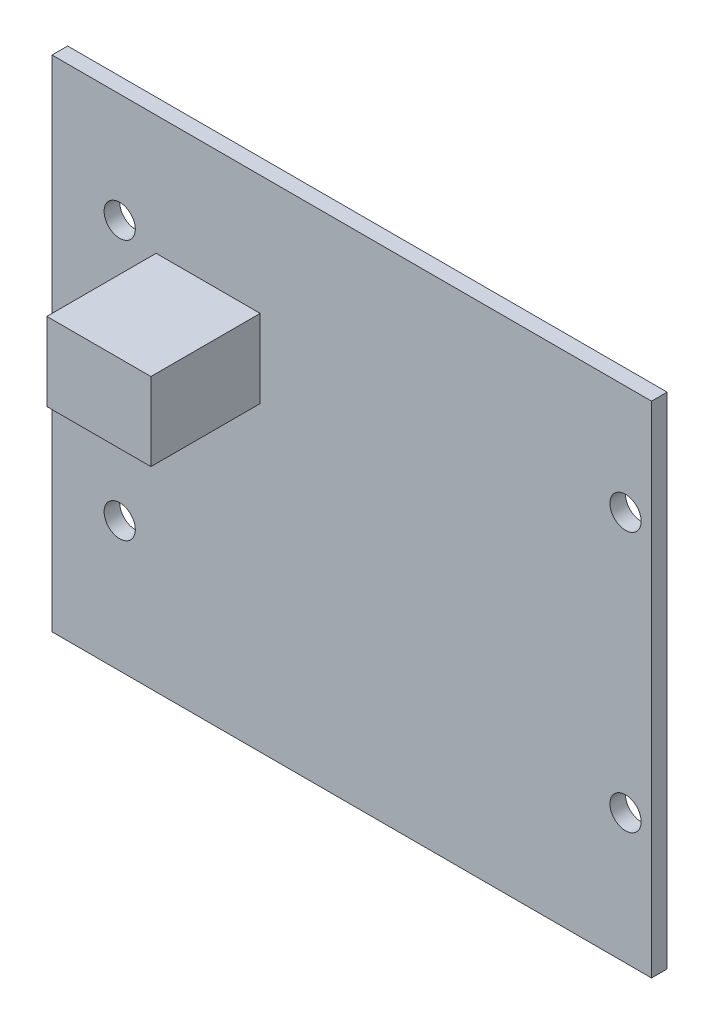
SolidWorks part; units mm, degrees
ref_plane "Přední rovina" through (0, 0, 0) normal (0, 0, 1) x (1, 0, 0)
ref_plane "Horní rovina" through (0, 0, 0) normal (0, 1, 0) x (1, 0, 0)
ref_plane "Pravá rovina" through (0, 0, 0) normal (1, 0, 0) x (0, 0, -1)
sketch "Skica1" plane through (0, 0, 0) normal (0, 0, 1) x (1, 0, 0)
  line L1 (0, 0) -> (57.6, 0)
  line L2 (0, 0) -> (0, 48)
  line L3 (0, 48) -> (57.6, 48)
  line L4 (57.6, 0) -> (57.6, 48)
  circle A0 centre (6.5, 37.5) radius 1.5
  circle A1 centre (6.5, 12.5) radius 1.5
  circle A2 centre (55.1, 37.5) radius 1.5
  circle A3 centre (55.1, 12.5) radius 1.5
  dimension "D3" = 3
  dimension "D1" = 57.6
  dimension "D2" = 48
  dimension "D4" = 2.5
  dimension "D5" = 6.5
  dimension "D6" = 6.5
  dimension "D7" = 12.5
  dimension "D8" = 12.5
  dimension "D9" = 2.5
  dimension "D10" = 37.5
  dimension "D11" = 37.5
extrude "Přidat vysunutím1" add sketch "Skica1" along normal blind 1.5
sketch "Skica2" plane through (0, 0, 1.5) normal (0, 0, 1) x (1, 0, 0)
  line L0 (0, 48) -> (0, 0) construction
  line L1 (10, 36.5) -> (20, 36.5)
  line L2 (10, 36.5) -> (10, 29)
  line L3 (10, 29) -> (20, 29)
  line L4 (20, 36.5) -> (20, 29)
  line L5 (0, 0) -> (57.6, 0) construction
  dimension "D1" = 10
  dimension "D2" = 7.5
  dimension "D3" = 10
  dimension "D4" = 29
extrude "Přidat vysunutím2" add sketch "Skica2" along normal blind 10.5
sketch "Skica3" plane through (0, 0, 1.5) normal (0, 0, 1) x (1, 0, 0)
  line L0 (0, 0) -> (57.6, 0) construction
  line L1 (12, 2) -> (24, 2)
  line L2 (12, 2) -> (12, 7)
  line L3 (12, 7) -> (24, 7)
  line L4 (24, 2) -> (24, 7)
  line L5 (35.6, 47) -> (52.6, 47)
  line L6 (35.6, 47) -> (35.6, 4)
  line L7 (35.6, 4) -> (52.6, 4)
  line L8 (52.6, 47) -> (52.6, 4)
  line L9 (0, 48) -> (0, 0) construction
  line L10 (57.6, 0) -> (57.6, 48) construction
  dimension "D1" = 5
  dimension "D2" = 12
  dimension "D3" = 2
  dimension "D4" = 12
  dimension "D5" = 17
  dimension "D6" = 43
  dimension "D7" = 4
  dimension "D8" = 5
